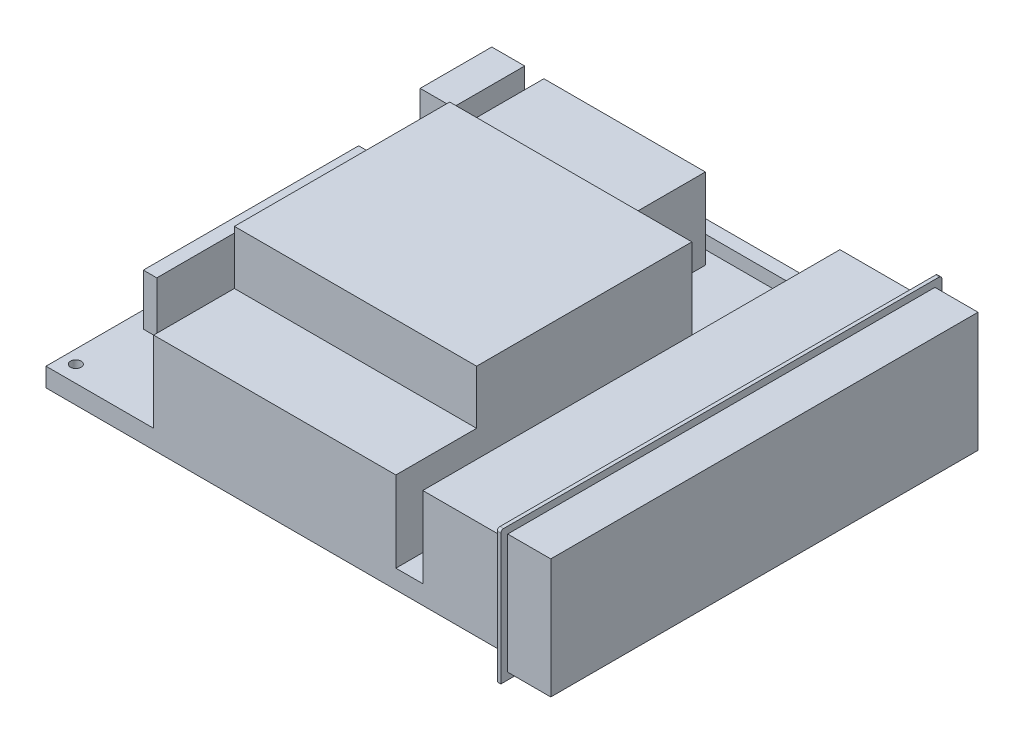
SolidWorks part; units mm, degrees
ref_plane "Front Plane" through (0, 0, 0) normal (0, 0, 1) x (1, 0, 0)
ref_plane "Top Plane" through (0, 0, 0) normal (0, 1, 0) x (1, 0, 0)
ref_plane "Right Plane" through (0, 0, 0) normal (1, 0, 0) x (0, 0, -1)
sketch "Sketch1" plane through (0, 0, 0) normal (0, 1, 0) x (1, 0, 0)
  line L1 (-85, -85) -> (85, -85)
  line L2 (-85, -85) -> (-85, 85)
  line L3 (-85, 85) -> (85, 85)
  line L4 (85, -85) -> (85, 85)
  line L5 (-85, -85) -> (85, 85) construction
  line L6 (-85, 85) -> (85, -85) construction
  point P0 (0, 0)
  dimension "D1" = 170
extrude "alusplaat" add sketch "Sketch1" along normal blind 2
sketch "Sketch2" plane through (0, 2, 0) normal (0, 1, 0) x (-1, 0, 0)
  line L1 (-85, 85) -> (-55, 85)
  line L2 (-85, 85) -> (-85, -70)
  line L3 (-85, -70) -> (-55, -70)
  line L4 (-55, 85) -> (-55, -70)
  dimension "D1" = 155
  dimension "D2" = 30
extrude "pistikud" add sketch "Sketch2" along normal blind 35
sketch "Sketch3" plane through (0, 2, 0) normal (0, 1, 0) x (1, 0, 0)
  line L0 (-85, -85) -> (55, -85) construction
  line L1 (-45, -85) -> (45, -85)
  line L2 (-45, -85) -> (-45, 25)
  line L3 (-45, 25) -> (45, 25)
  line L4 (45, -85) -> (45, 25)
  line L5 (-85, 85) -> (-85, -85) construction
  dimension "D1" = 90
  dimension "D2" = 40
  dimension "D3" = 110
extrude "cpu+mälud" add sketch "Sketch3" along normal blind 55
sketch "Sketch4" plane through (0, 2, 0) normal (0, 1, 0) x (1, 0, 0)
  line L1 (5, 35) -> (-55, 35)
  line L2 (5, 35) -> (5, 70)
  line L3 (5, 70) -> (-55, 70)
  line L4 (-55, 35) -> (-55, 70)
  line L5 (-85, 85) -> (-85, -85) construction
  line L6 (85, 85) -> (-85, 85) construction
  dimension "D1" = 35
  dimension "D2" = 60
  dimension "D3" = 30
  dimension "D4" = 15
extrude "sinine radikas" add sketch "Sketch4" along normal blind 35
sketch "Sketch5" plane through (0, 2, 0) normal (0, 1, 0) x (-1, 0, 0)
  line L0 (85, -85) -> (85, 85) construction
  line L1 (45, -75) -> (-45, -75)
  line L2 (45, -75) -> (45, -80)
  line L3 (45, -80) -> (-45, -80)
  line L4 (-45, -75) -> (-45, -80)
  line L5 (-85, -85) -> (85, -85) construction
  dimension "D1" = 90
  dimension "D2" = 40
  dimension "D3" = 5
  dimension "D4" = 5
extrude "pcie pesa" add sketch "Sketch5" along normal blind 10
sketch "Sketch6" plane through (0, 2, 0) normal (0, 1, 0) x (-1, 0, 0)
  line L1 (67.672, -48.9124) -> (79.8888, -48.9124)
  line L2 (67.672, -48.9124) -> (67.672, -75.5395)
  line L3 (67.672, -75.5395) -> (79.8888, -75.5395)
  line L4 (79.8888, -48.9124) -> (79.8888, -75.5395)
extrude "raid pesad" add sketch "Sketch6" along normal blind 30
sketch "Sketch7" plane through (0, 2, 0) normal (0, 1, 0) x (-1, 0, 0)
  line L1 (85, -85) -> (-85, -85)
  line L2 (85, -85) -> (85, 85)
  line L3 (85, 85) -> (-85, 85)
  line L4 (-85, -85) -> (-85, 85)
extrude "üleüldine müra" add sketch "Sketch7" along normal blind 5
sketch "Sketch8" plane through (0, 7, 0) normal (0, 1, 0) x (-1, 0, 0)
  line L0 (-85, -85) -> (85, -85) construction
  line L1 (78.8401, -25) -> (73.8401, -25)
  line L2 (78.8401, -25) -> (78.8401, 55)
  line L3 (78.8401, 55) -> (73.8401, 55)
  line L4 (73.8401, -25) -> (73.8401, 55)
  dimension "D1" = 5
  dimension "D2" = 80
  dimension "D3" = 60
extrude "patrei ja igasugused lülitid" add sketch "Sketch8" along normal blind 19
sketch "Sketch9" plane through (0, 57, 0) normal (0, 1, 0) x (-1, 0, 0)
  line L0 (-45, 85) -> (-45, -25) construction
  line L1 (45, -25) -> (-45, -25)
  line L2 (45, -25) -> (45, 55)
  line L3 (45, 55) -> (-45, 55)
  line L4 (-45, -25) -> (-45, 55)
  dimension "D1" = 80
extrude "mälud" cut sketch "Sketch9" against normal blind 20 flip side to cut
sketch "Sketch10" plane through (0, 7, 0) normal (0, 1, 0) x (1, 0, 0)
  line L0 (85, 85) -> (-85, 85) construction
  line L1 (74.84, 78.65) -> (-80.1, 78.65) construction
  line L2 (74.84, 78.65) -> (74.84, -78.83) construction
  line L3 (74.84, -78.83) -> (-80.1, -78.83) construction
  line L4 (-80.1, 78.65) -> (-80.1, -78.83) construction
  line L5 (85, 70) -> (85, 85) construction
  circle A0 centre (74.84, 78.65) radius 1.98
  circle A1 centre (-80.1, 78.65) radius 1.98
  circle A2 centre (-80.1, -78.83) radius 1.98
  circle A3 centre (51.98, -78.83) radius 1.98
  dimension "D6" = 3.96
  dimension "D1" = 6.35
  dimension "D2" = 10.16
  dimension "D3" = 154.94
  dimension "D4" = 157.48
  dimension "D5" = 22.86
extrude "Cut-Extrude2" cut sketch "Sketch10" against normal up to next
sketch "Sketch13" plane through (0, 7, 0) normal (0, 1, 0) x (1, 0, 0)
  line L1 (74.84, 78.65) -> (87.11, 78.65)
  line L2 (74.84, 78.65) -> (74.84, -92.9265)
  line L3 (74.84, -92.9265) -> (87.11, -92.9265)
  line L4 (87.11, 78.65) -> (87.11, -92.9265)
  dimension "D1" = 12.27
ref_plane "Plane2" through (87.11, 0, 0) normal (1, 0, 0) x (0, 0, -1)
sketch "Sketch11" plane through (87.11, 0, 0) normal (1, 0, 0) x (0, 0, -1)
  line L0 (-85, 0) -> (85, 0) construction
  line L1 (-86.875, -3.81) -> (71.875, -3.81) construction
  line L2 (-86.875, -3.81) -> (-86.875, 40.64) construction
  line L3 (-86.875, 40.64) -> (71.875, 40.64) construction
  line L4 (71.875, -3.81) -> (71.875, 40.64) construction
  line L5 (-88.415, 43.18) -> (73.415, 43.18)
  line L6 (71.875, 18.415) -> (70, 18.415) construction
  line L7 (70, 37) -> (70, 7) construction
  line L8 (-86.875, 18.415) -> (-85, 18.415) construction
  line L9 (-85, 37) -> (-85, 0) construction
  line L10 (74.415, -5.35) -> (74.415, 42.18)
  line L11 (-89.415, -6.35) -> (73.415, -6.35)
  line L12 (-89.415, -6.35) -> (-89.415, 42.18)
  line L13 (-89.415, -6.35) -> (74.415, -6.35) construction
  line L14 (74.415, -6.35) -> (74.415, 43.18) construction
  line L15 (-89.415, 43.18) -> (74.415, 43.18) construction
  line L16 (-89.415, -6.35) -> (-89.415, 43.18) construction
  arc A0 (73.415, -6.35) -> (74.415, -5.35) centre (73.415, -5.35) ccw
  arc A1 (74.415, 42.18) -> (73.415, 43.18) centre (73.415, 42.18) ccw
  arc A2 (-88.415, 43.18) -> (-89.415, 42.18) centre (-88.415, 42.18) ccw
  dimension "D5" = 1
  dimension "D1" = 158.75
  dimension "D2" = 44.45
  dimension "D3" = 3.81
  dimension "D4" = 2.54
extrude "Boss-Extrude1" add sketch "Sketch11" along normal blind 1.32
sketch "Sketch12" plane through (88.43, 0, 0) normal (1, 0, 0) x (0, 0, -1)
  line L1 (-86.875, -3.81) -> (71.875, -3.81)
  line L2 (-86.875, -3.81) -> (-86.875, 40.64)
  line L3 (-86.875, 40.64) -> (71.875, 40.64)
  line L4 (71.875, -3.81) -> (71.875, 40.64)
  line L5 (-88.415, 43.18) -> (73.415, 43.18)
  line L10 (74.415, -5.35) -> (74.415, 42.18)
  line L11 (-89.415, -6.35) -> (73.415, -6.35)
  line L12 (-89.415, -6.35) -> (-89.415, 42.18)
  line L13 (-89.415, -6.35) -> (74.415, -6.35) construction
  line L14 (74.415, -6.35) -> (74.415, 43.18) construction
  line L15 (-89.415, 43.18) -> (74.415, 43.18) construction
  line L16 (-89.415, -6.35) -> (-89.415, 43.18) construction
  arc A0 (73.415, -6.35) -> (74.415, -5.35) centre (73.415, -5.35) ccw
  arc A1 (74.415, 42.18) -> (73.415, 43.18) centre (73.415, 42.18) ccw
  arc A2 (-88.415, 43.18) -> (-89.415, 42.18) centre (-88.415, 42.18) ccw
  arc A5 (-88.415, 43.18) -> (-89.415, 42.18) centre (-88.415, 42.18) ccw construction
  dimension "D5" = 1
  dimension "D1" = 158.75
  dimension "D2" = 44.45
  dimension "D4" = 2.54
extrude "Boss-Extrude2" add sketch "Sketch12" along normal blind 16 contours L1 L4 L3 L2
